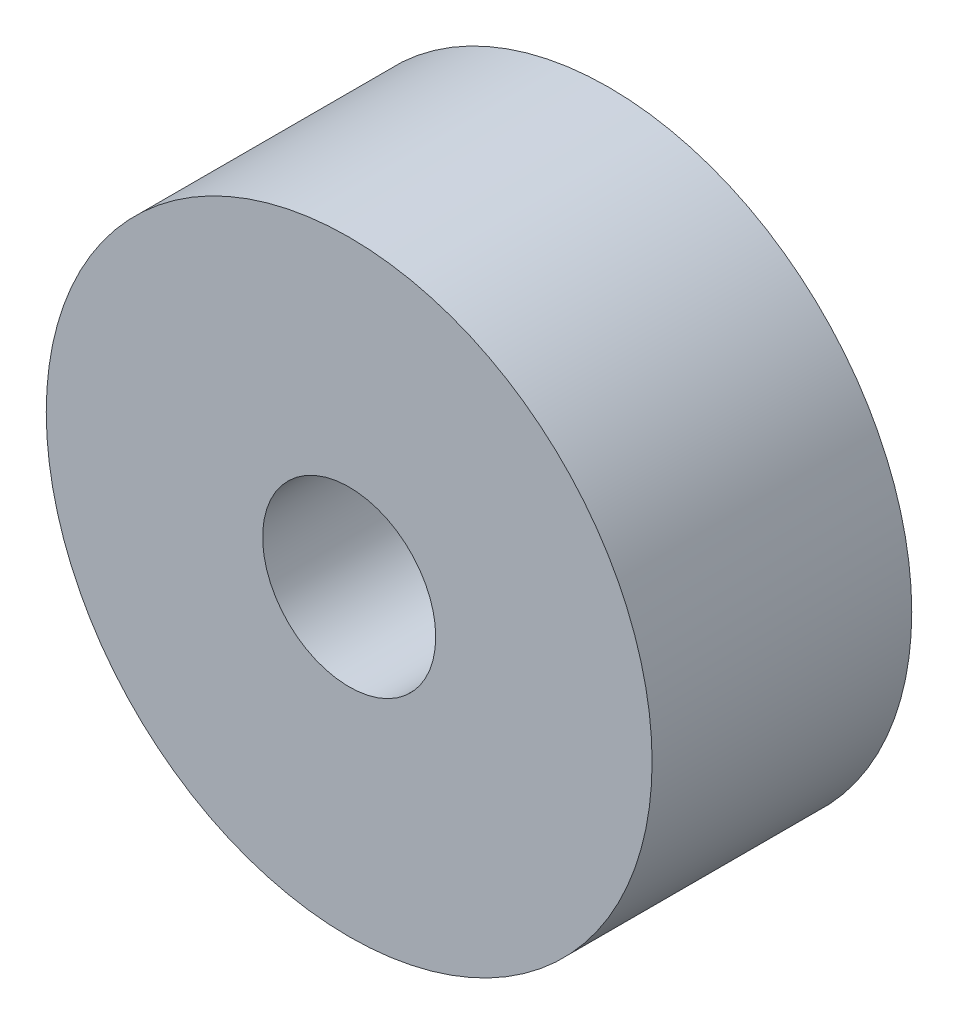
SolidWorks part; units mm, degrees
ref_plane "Спереди" through (0, 0, 0) normal (0, 0, 1) x (1, 0, 0)
ref_plane "Сверху" through (0, 0, 0) normal (0, 1, 0) x (1, 0, 0)
ref_plane "Справа" through (0, 0, 0) normal (1, 0, 0) x (0, 0, -1)
sketch "Эскиз1" plane through (0, 0, 0) normal (0, 0, 1) x (1, 0, 0)
  circle A0 centre (0, 0) radius 35
  circle A1 centre (0, 0) radius 10
extrude "Carrier" add sketch "Эскиз1" along normal blind 30 from offset 15
